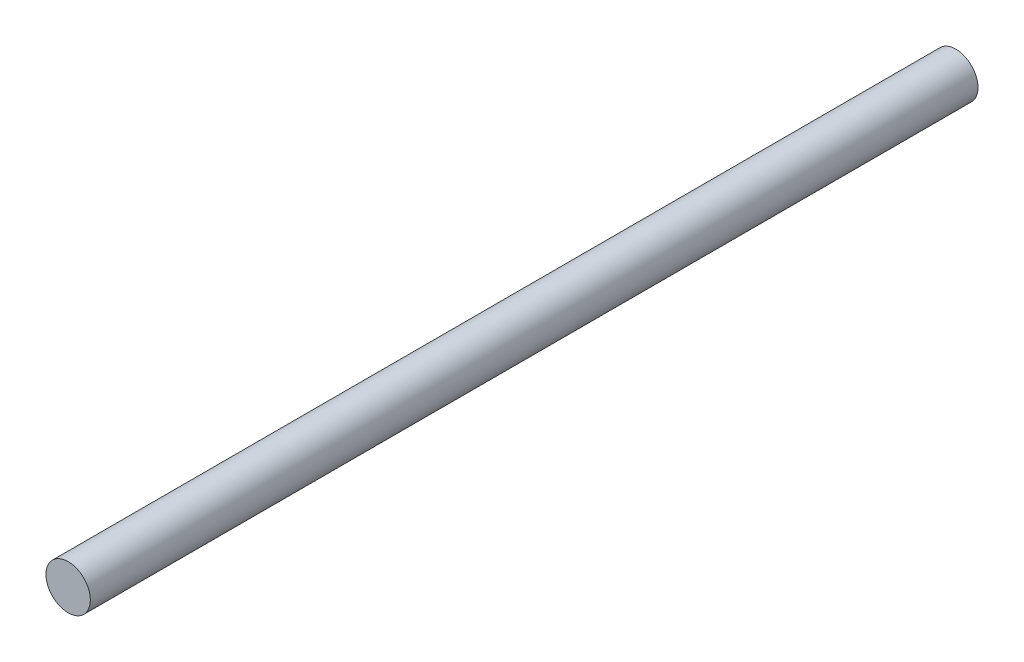
SolidWorks part; units mm, degrees
material "1023 Carbon Steel Sheet (SS)"
ref_plane "Front Plane" through (0, 0, 0) normal (0, 0, 1) x (1, 0, 0)
ref_plane "Top Plane" through (0, 0, 0) normal (0, 1, 0) x (1, 0, 0)
ref_plane "Right Plane" through (0, 0, 0) normal (1, 0, 0) x (0, 0, -1)
sketch "Sketch1" plane through (0, 0, 0) normal (0, 0, 1) x (1, 0, 0)
  circle A0 centre (0, 0) radius 6.35
  dimension "D1" = 12.7
extrude "Boss-Extrude1" add sketch "Sketch1" along normal blind 254
